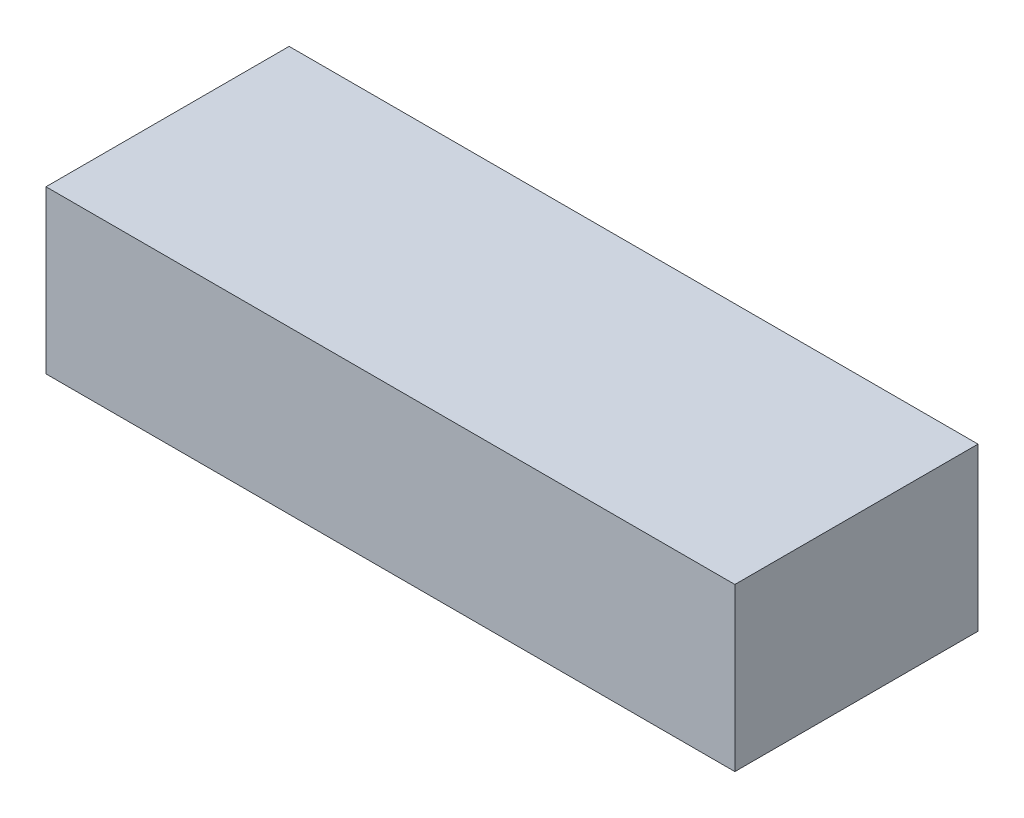
SolidWorks part; units mm, degrees
ref_plane "Alzado" through (0, 0, 0) normal (0, 0, 1) x (1, 0, 0)
ref_plane "Planta" through (0, 0, 0) normal (0, 1, 0) x (1, 0, 0)
ref_plane "Vista lateral" through (0, 0, 0) normal (1, 0, 0) x (0, 0, -1)
sketch "Croquis1" plane through (0, 0, 0) normal (0, 1, 0) x (1, 0, 0)
  line L1 (-34, -12) -> (34, -12)
  line L2 (-34, -12) -> (-34, 12)
  line L3 (-34, 12) -> (34, 12)
  line L4 (34, -12) -> (34, 12)
  line L5 (-34, -12) -> (34, 12) construction
  line L6 (-34, 12) -> (34, -12) construction
  point P0 (0, 0)
  dimension "D1" = 68
  dimension "D2" = 24
extrude "Saliente-Extruir1" add sketch "Croquis1" along normal blind 16
